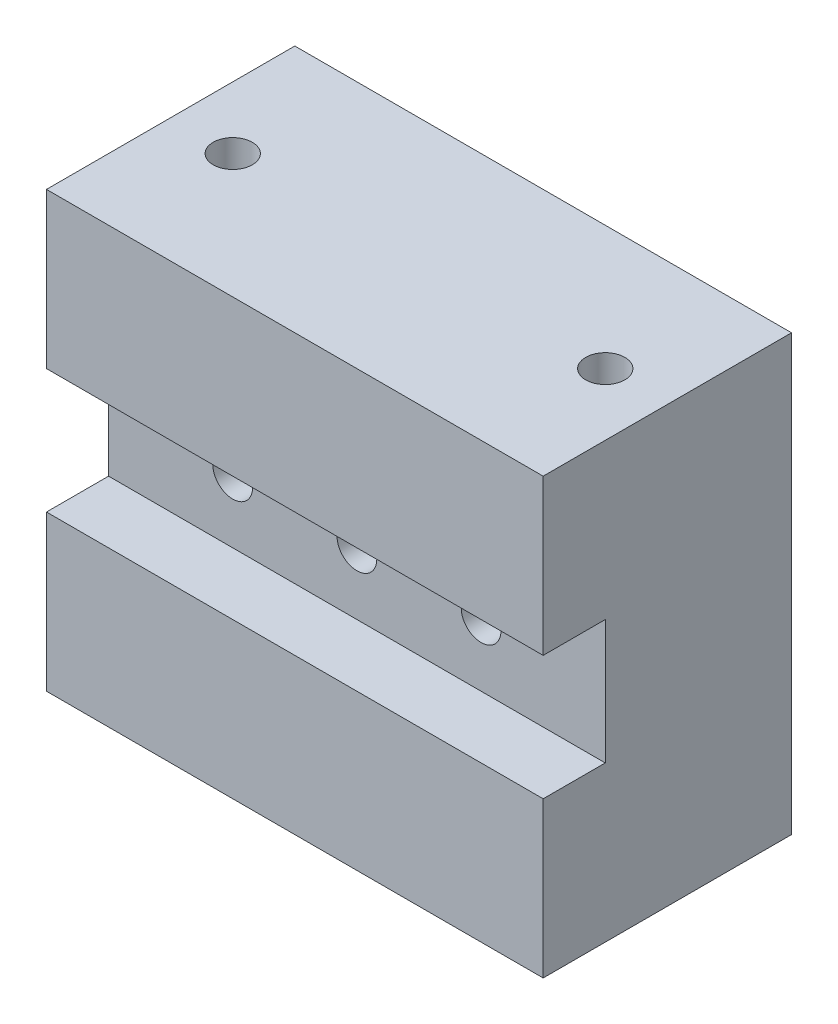
SolidWorks part; units mm, degrees
material "ABS"
ref_plane "Front Plane" through (0, 0, 0) normal (0, 0, 1) x (1, 0, 0)
ref_plane "Top Plane" through (0, 0, 0) normal (0, 1, 0) x (1, 0, 0)
ref_plane "Right Plane" through (0, 0, 0) normal (1, 0, 0) x (0, 0, -1)
sketch "Sketch1" plane through (0, 0, 0) normal (0, 0, 1) x (1, 0, 0)
  line L1 (0, 0) -> (50.8, 0)
  line L2 (0, 0) -> (0, 44.45)
  line L3 (0, 44.45) -> (50.8, 44.45)
  line L4 (50.8, 0) -> (50.8, 44.45)
  dimension "D1" = 50.8
  dimension "D2" = 44.45
extrude "Boss-Extrude1" add sketch "Sketch1" along normal blind 25.4
sketch "Sketch4" plane through (0, 44.45, 0) normal (0, 1, 0) x (1, 0, 0)
  line L0 (50.8, -25.4) -> (0, -25.4) construction
  line L1 (0, -25.4) -> (0, 0) construction
  circle A0 centre (6.35, -12.7) radius 2
  circle A1 centre (44.45, -12.7) radius 2
  dimension "D1" = 4
  dimension "D2" = 12.7
  dimension "D3" = 38.1
  dimension "D4" = 6.35
extrude "Cut-Extrude3" cut sketch "Sketch4" against normal through all
sketch "Sketch5" plane through (0, 0, 25.4) normal (0, 0, 1) x (1, 0, 0)
  line L0 (0, 44.45) -> (0, 0) construction
  line L1 (0, 15.875) -> (50.8, 15.875)
  line L2 (0, 15.875) -> (0, 28.575)
  line L3 (0, 28.575) -> (50.8, 28.575)
  line L4 (50.8, 15.875) -> (50.8, 28.575)
  line L5 (50.8, 0) -> (50.8, 44.45) construction
  line L6 (50.8, 44.45) -> (0, 44.45) construction
  dimension "D1" = 12.7
  dimension "D2" = 15.875
extrude "Cut-Extrude4" cut sketch "Sketch5" against normal blind 6.35
sketch "Sketch6" plane through (0, 0, 19.05) normal (0, 0, 1) x (1, 0, 0)
  line L0 (0, 28.575) -> (0, 15.875) construction
  line L1 (0, 15.875) -> (50.8, 15.875) construction
  circle A0 centre (25.4, 22.225) radius 2.032
  circle A1 centre (38.1, 22.225) radius 2.032
  circle A2 centre (12.7, 22.225) radius 2.032
  dimension "D6" = 4.064
  dimension "D1" = 12.7
  dimension "D2" = 12.7
  dimension "D3" = 12.7
  dimension "D4" = 6.35
extrude "Cut-Extrude5" cut sketch "Sketch6" against normal through all
